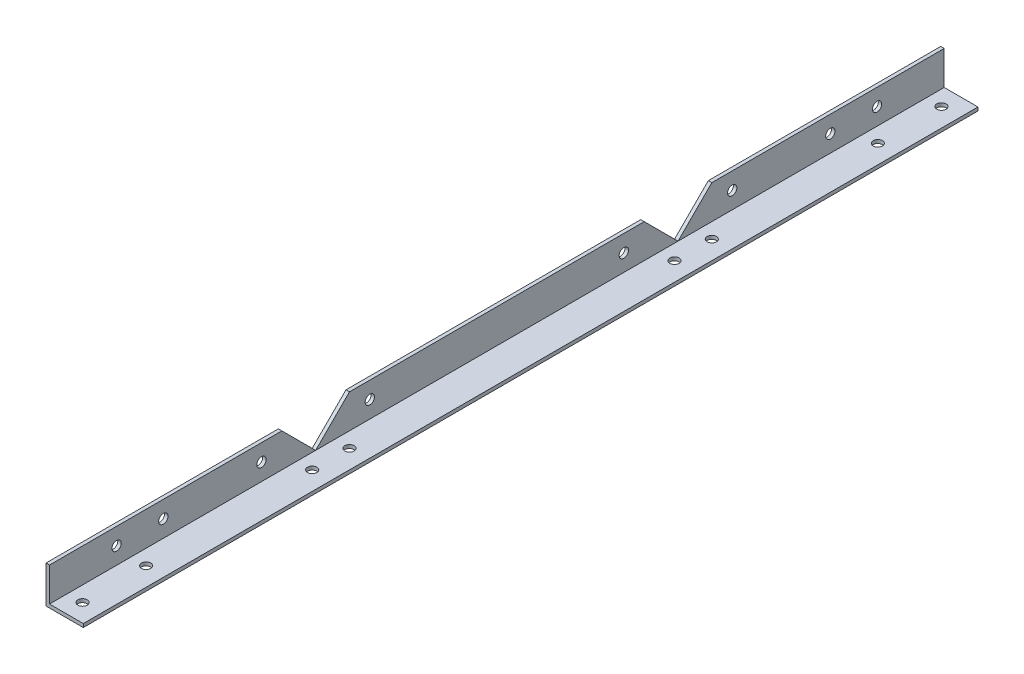
SolidWorks part; units mm, degrees
ref_plane "Front Plane" through (0, 0, 0) normal (0, 0, 1) x (1, 0, 0)
ref_plane "Top Plane" through (0, 0, 0) normal (0, 1, 0) x (1, 0, 0)
ref_plane "Right Plane" through (0, 0, 0) normal (1, 0, 0) x (0, 0, -1)
sketch "Sketch1" plane through (0, 0, 0) normal (0, 0, 1) x (1, 0, 0)
  line L0 (0, 0) -> (0, 17.272)
  line L1 (0, 17.272) -> (-1.778, 17.272)
  line L2 (-1.778, 17.272) -> (-1.778, -1.778)
  line L3 (-1.778, -1.778) -> (17.272, -1.778)
  line L4 (17.272, -1.778) -> (17.272, 0)
  line L5 (17.272, 0) -> (0, 0)
  dimension "D1" = 1.778
  dimension "D2" = 1.778
  dimension "D3" = 19.05
  dimension "D4" = 19.05
extrude "Boss-Extrude1" add sketch "Sketch1" along normal blind 208.28
sketch "Sketch2" plane through (0, 0, 0) normal (1, 0, 0) x (0, 0, -1)
  line L0 (-92.583, 0) -> (-109.855, 17.272)
  line L1 (-208.28, 0) -> (0, 0) construction
  line L2 (-208.28, 17.272) -> (0, 17.272) construction
  line L3 (-109.855, 17.272) -> (-75.311, 17.272)
  line L4 (-75.311, 17.272) -> (-92.583, 0)
  line L5 (-208.28, 0) -> (0, 0) construction
  line L6 (-208.28, 0) -> (-208.28, 17.272) construction
  circle A0 centre (-194.31, 8.636) radius 2.3813
  circle A1 centre (-170.434, 8.636) radius 2.3813
  circle A2 centre (-120.269, 8.636) radius 2.3813
  circle A3 centre (-64.897, 8.636) radius 2.3813
  dimension "D8" = 4.7625
  dimension "D9" = 4.7625
  dimension "D10" = 4.7625
  dimension "D11" = 4.7625
  dimension "D13" = 23.876
  dimension "D14" = 10.414
  dimension "D15" = 10.414
  dimension "D1" = 45
  dimension "D2" = 45
  dimension "D3" = 115.697
  dimension "D4" = 8.636
  dimension "D5" = 8.636
  dimension "D6" = 8.636
  dimension "D7" = 8.636
  dimension "D12" = 13.97
extrude "Cut-Extrude1" cut sketch "Sketch2" against normal up to surface (1.778 mm away) up to face at (-1.778, 7.747, 104.14)
sketch "Sketch3" plane through (0, 0, 208.28) normal (0, 0, 1) x (1, 0, 0)
  line L1 (-1.778, -1.778) -> (17.272, -1.778)
  line L2 (-1.778, -1.778) -> (-1.778, 0)
  line L3 (-1.778, 0) -> (17.272, 0)
  line L4 (17.272, -1.778) -> (17.272, 0)
  line L5 (-1.778, 17.272) -> (0, 17.272)
  line L6 (-1.778, 17.272) -> (-1.778, 0)
  line L7 (-1.778, 0) -> (0, 0)
  line L8 (0, 17.272) -> (0, 0)
extrude "Boss-Extrude2" add sketch "Sketch3" along normal blind 20.32 contours L2 L1 L4 L3 | L7 L8 L5 L6
sketch "Sketch4" plane through (0, 0, 0) normal (0, 1, 0) x (1, 0, 0)
  line L0 (17.272, -228.6) -> (0, -228.6) construction
  line L2 (0, -92.583) -> (0, 0) construction
  line L4 (0, -228.6) -> (0, -92.583) construction
  line L6 (0, -228.6) -> (17.272, -228.6) construction
  circle A0 centre (7.747, -219.456) radius 2.3812
  circle A1 centre (7.747, -83.058) radius 2.3813
  circle A2 centre (7.747, -102.108) radius 2.3813
  circle A3 centre (7.747, -186.944) radius 2.3813
  dimension "D1" = 9.144
  dimension "D2" = 4.7625
  dimension "D4" = 4.7625
  dimension "D9" = 4.7625
  dimension "D10" = 41.656
  dimension "D11" = 4.7625
  dimension "D12" = 7.747
  dimension "D3" = 7.747
  dimension "D5" = 9.525
  dimension "D6" = 7.747
  dimension "D7" = 7.747
  dimension "D8" = 9.525
extrude "Cut-Extrude2" cut sketch "Sketch4" against normal up to surface (1.778 mm away) up to face at (7.747, -1.778, 114.3)
mirror "Mirror3" about plane through (0, 0, 0) normal (0, 0, -1) of "Cut-Extrude2", "Boss-Extrude2", "Cut-Extrude1", "Boss-Extrude1"
